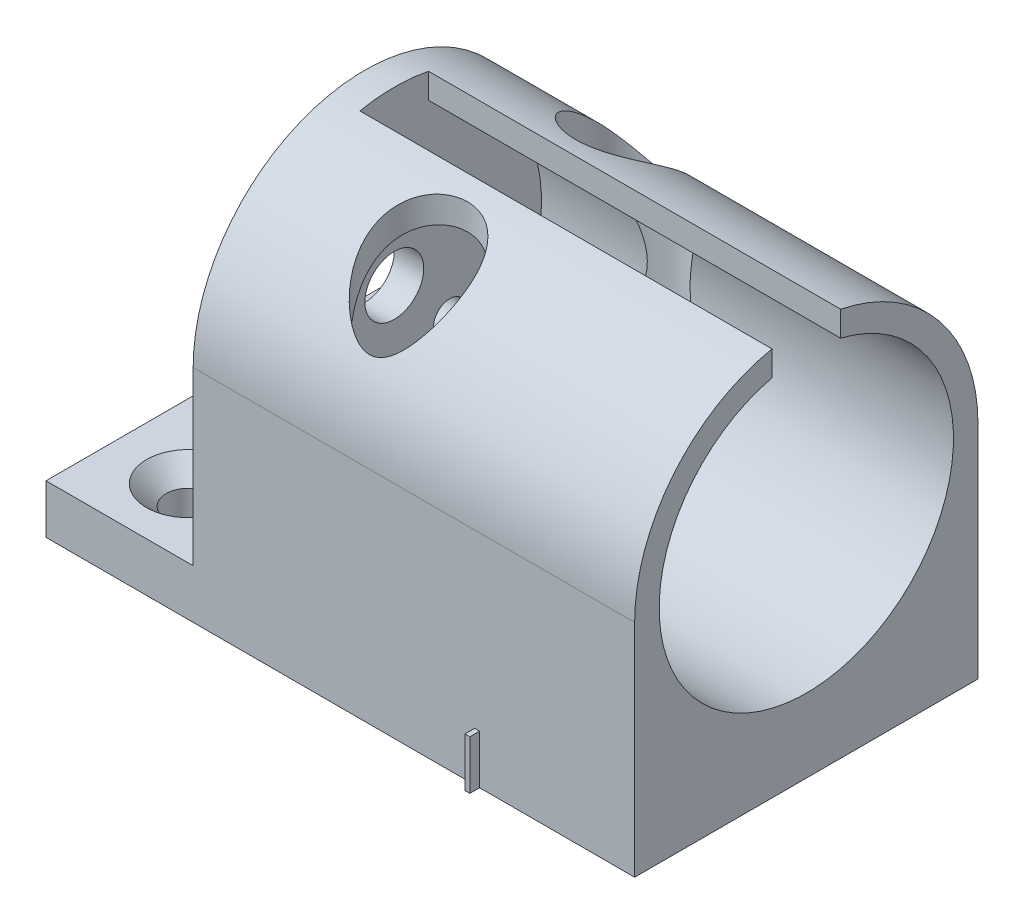
SolidWorks part; units mm, degrees
ref_plane "Front Plane" through (0, 0, 0) normal (0, 0, 1) x (1, 0, 0)
ref_plane "Top Plane" through (0, 0, 0) normal (0, 1, 0) x (1, 0, 0)
ref_plane "Right Plane" through (0, 0, 0) normal (1, 0, 0) x (0, 0, -1)
sketch "Sketch1" plane through (0, 0, 0) normal (0, 0, 1) x (1, 0, 0)
  line L0 (0.5, -17.5) -> (15.5, -17.5)
  line L1 (15.5, -17.5) -> (15.5, 17.5)
  line L2 (15.5, 17.5) -> (18.5, 17.5)
  line L3 (18.5, 17.5) -> (18.5, -17.5)
  line L4 (18.5, -17.5) -> (60.5, -17.5)
  line L5 (60.5, -17.5) -> (60.5, -22.5)
  line L9 (0.5, -22.5) -> (0.5, -17.5)
  line L10 (0.5, -22.5) -> (60.5, -22.5)
  line L15 (15, 5.6084) -> (15, -6.1785) construction
  point P14 (15.5, 0)
  dimension "D1" = 5
  dimension "D3" = 42
  dimension "D4" = 15
  dimension "D5" = 3
  dimension "D7" = 35
  dimension "D8" = 15
  dimension "D9" = 1
extrude "Boss-Extrude1" add sketch "Sketch1" along normal mid plane 35
sketch "Sketch2" plane through (0, 0, 17.5) normal (0, 0, 1) x (1, 0, 0)
  line L0 (60.5, -17.5) -> (18.5, -17.5) construction
  line L1 (44.2, -17.5) -> (44.7, -17.5)
  line L2 (44.2, -17.5) -> (44.2, -22.5)
  line L3 (44.2, -22.5) -> (44.7, -22.5)
  line L4 (44.7, -17.5) -> (44.7, -22.5)
  line L5 (0.5, -22.5) -> (60.5, -22.5) construction
  point P8 (44.45, -17.5)
  dimension "D1" = 44.45
  dimension "D2" = 0.5
extrude "Boss-Extrude2" add sketch "Sketch2" against normal offset from surface (37 mm away) 1 from offset 1 up to face at (23.75, -10, -17.5) offset beyond the face yes
sketch "Sketch3" plane through (15.5, 0, 0) normal (-1, 0, 0) x (0, 0, 1)
  line L0 (-5.6569, -5.6569) -> (5.6569, -5.6569) construction
  line L1 (-5.6569, -5.6569) -> (-5.6569, 5.6569) construction
  line L2 (5.6569, -5.6569) -> (5.6569, 5.6569) construction
  line L3 (-5.6569, 5.6569) -> (5.6569, 5.6569) construction
  line L4 (-5.6569, -5.6569) -> (5.6569, 5.6569) construction
  line L5 (5.6569, -5.6569) -> (-5.6569, 5.6569) construction
  circle A0 centre (0, 0) radius 3
  circle A1 centre (-5.6569, 5.6569) radius 1.65
  circle A2 centre (5.6569, 5.6569) radius 1.65
  circle A3 centre (5.6569, -5.6569) radius 1.65
  circle A4 centre (-5.6569, -5.6569) radius 1.65
  dimension "D2" = 6
  dimension "D3" = 3.3
  dimension "D1" = 16
extrude "Cut-Extrude1" cut sketch "Sketch3" against normal through all
sketch "Sketch4" plane through (18.5, 0, 0) normal (1, 0, 0) x (0, 0, -1)
  line L1 (-17.5, 17.5) -> (17.5, 17.5)
  line L2 (-17.5, 17.5) -> (-17.5, -17.5)
  line L3 (-17.5, -17.5) -> (17.5, -17.5)
  line L4 (17.5, 17.5) -> (17.5, -17.5)
  circle A0 centre (0, 0) radius 15
  dimension "D1" = 30
extrude "Boss-Extrude3" add sketch "Sketch4" along normal through all
sketch "Sketch5" plane through (60.5, 0, 0) normal (1, 0, 0) x (0, 0, -1)
  line L0 (-17.5, -22.5) -> (-17.5, 17.5) construction
  line L1 (-17.5, 0) -> (-17.5, 18.5)
  line L2 (-17.5, 18.5) -> (17.5, 18.5)
  line L3 (17.5, 18.5) -> (17.5, 0)
  line L4 (17.5, 17.5) -> (-17.5, 17.5) construction
  arc A0 (-17.5, 0) -> (17.5, 0) centre (0, 0) cw
  dimension "D1" = 1
extrude "Cut-Extrude2" cut sketch "Sketch5" against normal through all
sketch "Sketch6" plane through (0, -17.5, 0) normal (0, 1, 0) x (1, 0, 0)
  line L0 (31.475, -10.5) -> (31.475, 10.5) construction
  line L1 (15.5, -17.5) -> (60.5, -17.5) construction
  line L2 (44.45, 0) -> (18.5, 0) construction
  line L3 (44.7, -18.5) -> (44.2, -18.5) construction
  line L4 (18.5, -15) -> (18.5, 15) construction
  circle A0 centre (31.475, -10.5) radius 5
  circle A1 centre (31.475, 10.5) radius 5
  point P4 (31.475, 0)
  point P7 (31.475, -15.5)
  point P14 (44.45, -18.5)
  point P15 (31.475, 0)
  dimension "D1" = 10
  dimension "D2" = 2
extrude "Cut-Extrude3" cut sketch "Sketch6" along normal through all
sketch "Sketch7" plane through (0, -17.5, 0) normal (0, 1, 0) x (1, 0, 0)
  line L0 (15.5, 17.5) -> (0.5, 17.5) construction
  line L1 (8, 10.5) -> (31.475, 10.5) construction
  line L2 (8, 10.5) -> (8, -10.5) construction
  line L3 (8, -10.5) -> (31.475, -10.5) construction
  line L4 (31.475, 10.5) -> (31.475, -10.5) construction
  circle A1 centre (31.475, 10.5) radius 5 construction
  circle A2 centre (8, 10.5) radius 2.25
  circle A3 centre (8, -10.5) radius 2.25
  circle A4 centre (31.475, -10.5) radius 2.25
  circle A5 centre (31.475, 10.5) radius 2.25
  point P4 (8, 0)
  point P12 (8, 17.5)
  dimension "D1" = 4.5
extrude "Cut-Extrude4" cut sketch "Sketch7" against normal through all
chamfer "Chamfer1" distance 2 angle 45 4 edges at (8, -17.5, 12.75) (8, -17.5, -8.25) (31.475, -17.5, 12.75) (31.475, -17.5, -8.25)
sketch "Sketch8" plane through (60.5, 0, 0) normal (1, 0, 0) x (0, 0, -1)
  line L1 (-3.5, 14.586) -> (3.5, 14.586)
  line L2 (-3.5, 14.586) -> (-3.5, 17.5)
  line L3 (-3.5, 17.5) -> (3.5, 17.5)
  line L4 (3.5, 14.586) -> (3.5, 17.5)
  circle A0 centre (0, 0) radius 15 construction
  circle A1 centre (0, 0) radius 15 construction
  arc A2 (17.5, 0) -> (-17.5, 0) centre (0, 0) ccw construction
  dimension "D1" = 7
extrude "Cut-Extrude5" cut sketch "Sketch8" against normal up to surface (42 mm away) up to face at (18.5, 0, 3)
